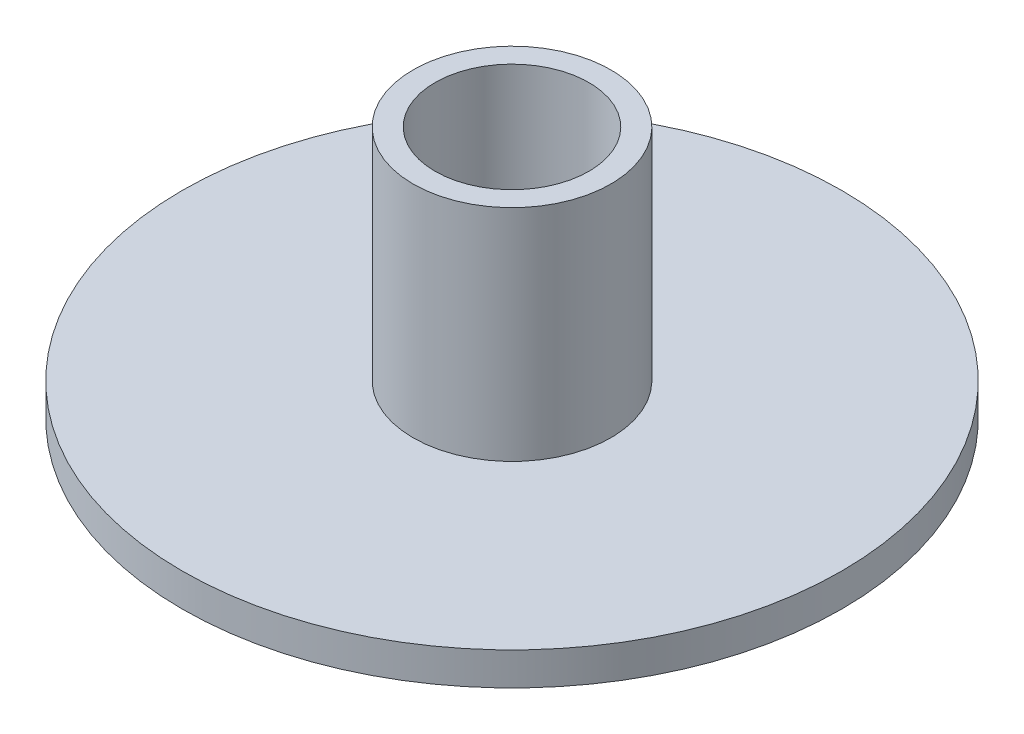
SolidWorks part; units mm, degrees
ref_plane "Front Plane" through (0, 0, 0) normal (0, 0, 1) x (1, 0, 0)
ref_plane "Top Plane" through (0, 0, 0) normal (0, 1, 0) x (1, 0, 0)
ref_plane "Right Plane" through (0, 0, 0) normal (1, 0, 0) x (0, 0, -1)
sketch "Sketch1" plane through (0, 0, 0) normal (1, 0, 0) x (0, 0, -1)
  line L0 (0, 28.0586) -> (0, -24.3494) construction
  line L5 (-9, 3.3739) -> (-30, 3.3739)
  line L6 (-30, 3.3739) -> (-30, 0.3739)
  line L14 (-9, 3.3739) -> (-9, 23.3739)
  line L15 (-9, 23.3739) -> (-7, 23.3739)
  line L24 (-7, 23.3739) -> (-7, 13.3739)
  line L25 (-7, 13.3739) -> (-5, 13.3739)
  line L26 (-5, 13.3739) -> (-5, 0.3739)
  line L27 (-5, 0.3739) -> (-30, 0.3739)
  dimension "D1" = 60
  dimension "D2" = 14
  dimension "D3" = 10
  dimension "D4" = 18
  dimension "D5" = 3
  dimension "D6" = 23
  dimension "D7" = 10
  dimension "D8" = 13
revolve "Revolve1" add sketch "Sketch1" angle 360 about L0
ref_plane "Plane1" through (0, 13.3739, 0) normal (0, 1, 0) x (1, 0, 0)
